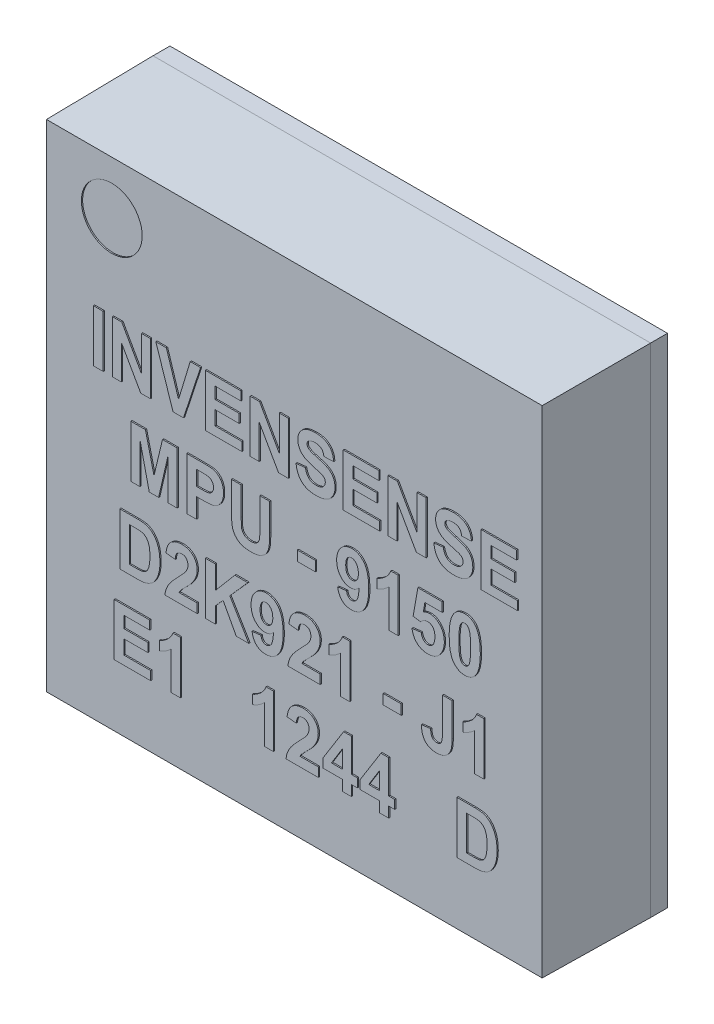
SolidWorks part; units mm, degrees
ref_plane "Front Plane" through (0, 0, 0) normal (0, 0, 1) x (1, 0, 0)
ref_plane "Top Plane" through (0, 0, 0) normal (0, 1, 0) x (1, 0, 0)
ref_plane "Right Plane" through (0, 0, 0) normal (1, 0, 0) x (0, 0, -1)
sketch "Sketch1" plane through (0, 0, 0) normal (0, 0, 1) x (1, 0, 0)
  line L1 (-2, -2) -> (2, -2)
  line L2 (-2, -2) -> (-2, 2)
  line L3 (-2, 2) -> (2, 2)
  line L4 (2, -2) -> (2, 2)
  line L5 (-2, -2) -> (2, 2) construction
  line L6 (-2, 2) -> (2, -2) construction
  point P0 (0, 0)
  dimension "D1" = 4
  dimension "D2" = 4
extrude "Boss-Extrude1" add sketch "Sketch1" along normal blind 0.864 draft 0.5 and the other way blind 0.136
sketch "Sketch2" plane through (0, 0, -0.136) normal (0, 0, -1) x (-1, 0, 0)
  line L0 (-0.875, -1.88) -> (-0.875, -1.53)
  line L1 (-1.25, -1.705) -> (1.25, -1.705) construction
  line L2 (-1.25, -1.705) -> (-1.25, 1.705) construction
  line L3 (-1.25, 1.705) -> (1.25, 1.705) construction
  line L4 (1.25, -1.705) -> (1.25, 1.705) construction
  line L5 (-1.25, -1.705) -> (1.25, 1.705) construction
  line L6 (-1.25, 1.705) -> (1.25, -1.705) construction
  line L7 (-1.375, -1.88) -> (-1.125, -1.88)
  line L8 (-1.375, -1.88) -> (-1.375, -1.53)
  line L9 (-1.375, -1.53) -> (-1.125, -1.53)
  line L10 (-1.125, -1.88) -> (-1.125, -1.53)
  line L11 (-1.375, -1.88) -> (-1.125, -1.53) construction
  line L12 (-1.375, -1.53) -> (-1.125, -1.88) construction
  line L13 (-0.875, -1.53) -> (-0.625, -1.53)
  line L14 (-0.625, -1.88) -> (-0.625, -1.53)
  line L15 (-0.875, -1.88) -> (-0.625, -1.88)
  line L16 (-0.375, -1.88) -> (-0.375, -1.53)
  line L17 (-0.375, -1.53) -> (-0.125, -1.53)
  line L18 (-0.125, -1.88) -> (-0.125, -1.53)
  line L19 (-0.375, -1.88) -> (-0.125, -1.88)
  line L20 (0.125, -1.88) -> (0.125, -1.53)
  line L21 (0.125, -1.53) -> (0.375, -1.53)
  line L22 (0.375, -1.88) -> (0.375, -1.53)
  line L23 (0.125, -1.88) -> (0.375, -1.88)
  line L24 (0.625, -1.88) -> (0.625, -1.53)
  line L25 (0.625, -1.53) -> (0.875, -1.53)
  line L26 (0.875, -1.88) -> (0.875, -1.53)
  line L27 (0.625, -1.88) -> (0.875, -1.88)
  line L28 (1.125, -1.88) -> (1.125, -1.53)
  line L29 (1.125, -1.53) -> (1.375, -1.53)
  line L30 (1.375, -1.88) -> (1.375, -1.53)
  line L31 (1.125, -1.88) -> (1.375, -1.88)
  line L32 (-1.88, 0.875) -> (-1.53, 0.875)
  line L33 (-1.88, 1.375) -> (-1.88, 1.125)
  line L34 (-1.88, 1.375) -> (-1.53, 1.375)
  line L35 (-1.53, 1.375) -> (-1.53, 1.125)
  line L36 (-1.88, 1.125) -> (-1.53, 1.125)
  line L37 (-1.53, 0.875) -> (-1.53, 0.625)
  line L38 (-1.88, 0.625) -> (-1.53, 0.625)
  line L39 (-1.88, 0.875) -> (-1.88, 0.625)
  line L40 (-1.88, 0.375) -> (-1.53, 0.375)
  line L41 (-1.53, 0.375) -> (-1.53, 0.125)
  line L42 (-1.88, 0.125) -> (-1.53, 0.125)
  line L43 (-1.88, 0.375) -> (-1.88, 0.125)
  line L44 (-1.88, -0.125) -> (-1.53, -0.125)
  line L45 (-1.53, -0.125) -> (-1.53, -0.375)
  line L46 (-1.88, -0.375) -> (-1.53, -0.375)
  line L47 (-1.88, -0.125) -> (-1.88, -0.375)
  line L48 (-1.88, -0.625) -> (-1.53, -0.625)
  line L49 (-1.53, -0.625) -> (-1.53, -0.875)
  line L50 (-1.88, -0.875) -> (-1.53, -0.875)
  line L51 (-1.88, -0.625) -> (-1.88, -0.875)
  line L52 (-1.88, -1.125) -> (-1.53, -1.125)
  line L53 (-1.53, -1.125) -> (-1.53, -1.375)
  line L54 (-1.88, -1.375) -> (-1.53, -1.375)
  line L55 (-1.88, -1.125) -> (-1.88, -1.375)
  line L56 (-1.88, 1.375) -> (-1.53, 1.125) construction
  line L57 (-1.53, 1.375) -> (-1.88, 1.125) construction
  line L58 (0.875, 1.88) -> (0.875, 1.53)
  line L59 (1.375, 1.88) -> (1.125, 1.88)
  line L60 (1.375, 1.88) -> (1.375, 1.53)
  line L61 (1.375, 1.53) -> (1.125, 1.53)
  line L62 (1.125, 1.88) -> (1.125, 1.53)
  line L63 (0.875, 1.53) -> (0.625, 1.53)
  line L64 (0.625, 1.88) -> (0.625, 1.53)
  line L65 (0.875, 1.88) -> (0.625, 1.88)
  line L66 (0.375, 1.88) -> (0.375, 1.53)
  line L67 (0.375, 1.53) -> (0.125, 1.53)
  line L68 (0.125, 1.88) -> (0.125, 1.53)
  line L69 (0.375, 1.88) -> (0.125, 1.88)
  line L70 (-0.125, 1.88) -> (-0.125, 1.53)
  line L71 (-0.125, 1.53) -> (-0.375, 1.53)
  line L72 (-0.375, 1.88) -> (-0.375, 1.53)
  line L73 (-0.125, 1.88) -> (-0.375, 1.88)
  line L74 (-0.625, 1.88) -> (-0.625, 1.53)
  line L75 (-0.625, 1.53) -> (-0.875, 1.53)
  line L76 (-0.875, 1.88) -> (-0.875, 1.53)
  line L77 (-0.625, 1.88) -> (-0.875, 1.88)
  line L78 (-1.125, 1.88) -> (-1.125, 1.53)
  line L79 (-1.125, 1.53) -> (-1.375, 1.53)
  line L80 (-1.375, 1.88) -> (-1.375, 1.53)
  line L81 (-1.125, 1.88) -> (-1.375, 1.88)
  line L82 (1.375, 1.88) -> (1.125, 1.53) construction
  line L83 (1.375, 1.53) -> (1.125, 1.88) construction
  line L84 (1.88, -0.875) -> (1.53, -0.875)
  line L85 (1.88, -1.375) -> (1.88, -1.125)
  line L86 (1.88, -1.375) -> (1.53, -1.375)
  line L87 (1.53, -1.375) -> (1.53, -1.125)
  line L88 (1.88, -1.125) -> (1.53, -1.125)
  line L89 (1.53, -0.875) -> (1.53, -0.625)
  line L90 (1.88, -0.625) -> (1.53, -0.625)
  line L91 (1.88, -0.875) -> (1.88, -0.625)
  line L92 (1.88, -0.375) -> (1.53, -0.375)
  line L93 (1.53, -0.375) -> (1.53, -0.125)
  line L94 (1.88, -0.125) -> (1.53, -0.125)
  line L95 (1.88, -0.375) -> (1.88, -0.125)
  line L96 (1.88, 0.125) -> (1.53, 0.125)
  line L97 (1.53, 0.125) -> (1.53, 0.375)
  line L98 (1.88, 0.375) -> (1.53, 0.375)
  line L99 (1.88, 0.125) -> (1.88, 0.375)
  line L100 (1.88, 0.625) -> (1.53, 0.625)
  line L101 (1.53, 0.625) -> (1.53, 0.875)
  line L102 (1.88, 0.875) -> (1.53, 0.875)
  line L103 (1.88, 0.625) -> (1.88, 0.875)
  line L104 (1.88, 1.125) -> (1.53, 1.125)
  line L105 (1.53, 1.125) -> (1.53, 1.375)
  line L106 (1.88, 1.375) -> (1.53, 1.375)
  line L107 (1.88, 1.125) -> (1.88, 1.375)
  line L108 (1.88, -1.375) -> (1.53, -1.125) construction
  line L109 (1.53, -1.375) -> (1.88, -1.125) construction
  point P0 (0, 0)
  point P105 (0, 0)
  dimension "D1" = 2.5
  dimension "D2" = 0.25
  dimension "D3" = 0.35
  dimension "D4" = 3.41
  dimension "D5" = 6
  dimension "D6" = 4
extrude "Boss-Extrude2" add sketch "Sketch2" along normal blind 0.01
sketch "Sketch3" plane through (0, 0, 0.864) normal (0, 0, 1) x (1, 0, 0)
  circle A0 centre (-1.4676, 1.5665) radius 0.2444
extrude "Cut-Extrude1" cut sketch "Sketch3" against normal blind 0.01
sketch "Sketch5" plane through (0, 0, 0.864) normal (0, 0, 1) x (1, 0, 0)
  line L0 (-1.6052, 0.4755) -> (-1.6052, 0.8946)
  line L1 (-1.6052, 0.8946) -> (-1.5271, 0.8946)
  line L2 (-1.5271, 0.8946) -> (-1.5271, 0.4755)
  line L3 (-1.5271, 0.4755) -> (-1.6052, 0.4755)
  line L4 (-1.453, 0.4755) -> (-1.453, 0.8946)
  line L5 (-1.453, 0.8946) -> (-1.3773, 0.8946)
  line L6 (-1.3773, 0.8946) -> (-1.2186, 0.6138)
  line L7 (-1.2186, 0.6138) -> (-1.2186, 0.8946)
  line L8 (-1.2186, 0.8946) -> (-1.1464, 0.8946)
  line L9 (-1.1464, 0.8946) -> (-1.1464, 0.4755)
  line L10 (-1.1464, 0.4755) -> (-1.2245, 0.4755)
  line L11 (-1.2245, 0.4755) -> (-1.3807, 0.751)
  line L12 (-1.3807, 0.751) -> (-1.3807, 0.4755)
  line L13 (-1.3807, 0.4755) -> (-1.453, 0.4755)
  line L14 (-0.9652, 0.4755) -> (-1.1033, 0.8946)
  line L15 (-1.1033, 0.8946) -> (-1.0189, 0.8946)
  line L16 (-1.0189, 0.8946) -> (-0.9209, 0.5844)
  line L17 (-0.9209, 0.5844) -> (-0.8269, 0.8946)
  line L18 (-0.8269, 0.8946) -> (-0.7439, 0.8946)
  line L19 (-0.7439, 0.8946) -> (-0.8811, 0.4755)
  line L20 (-0.8811, 0.4755) -> (-0.9652, 0.4755)
  line L21 (-0.7046, 0.4755) -> (-0.7046, 0.8946)
  line L22 (-0.7046, 0.8946) -> (-0.419, 0.8946)
  line L23 (-0.419, 0.8946) -> (-0.419, 0.8238)
  line L24 (-0.419, 0.8238) -> (-0.6264, 0.8238)
  line L25 (-0.6264, 0.8238) -> (-0.6264, 0.7307)
  line L26 (-0.6264, 0.7307) -> (-0.4336, 0.7307)
  line L27 (-0.4336, 0.7307) -> (-0.4336, 0.6599)
  line L28 (-0.4336, 0.6599) -> (-0.6264, 0.6599)
  line L29 (-0.6264, 0.6599) -> (-0.6264, 0.5463)
  line L30 (-0.6264, 0.5463) -> (-0.4115, 0.5463)
  line L31 (-0.4115, 0.5463) -> (-0.4115, 0.4755)
  line L32 (-0.4115, 0.4755) -> (-0.7046, 0.4755)
  line L33 (-0.3453, 0.4755) -> (-0.3453, 0.8946)
  line L34 (-0.3453, 0.8946) -> (-0.2696, 0.8946)
  line L35 (-0.2696, 0.8946) -> (-0.1109, 0.6138)
  line L36 (-0.1109, 0.6138) -> (-0.1109, 0.8946)
  line L37 (-0.1109, 0.8946) -> (-0.0387, 0.8946)
  line L38 (-0.0387, 0.8946) -> (-0.0387, 0.4755)
  line L39 (-0.0387, 0.4755) -> (-0.1168, 0.4755)
  line L40 (-0.1168, 0.4755) -> (-0.273, 0.751)
  line L41 (-0.273, 0.751) -> (-0.273, 0.4755)
  line L42 (-0.273, 0.4755) -> (-0.3453, 0.4755)
  line L43 (0.0234, 0.6113) -> (0.0993, 0.6195)
  line L44 (0.3256, 0.7741) -> (0.2475, 0.7711)
  line L45 (0.4031, 0.4755) -> (0.4031, 0.8946)
  line L46 (0.4031, 0.8946) -> (0.6887, 0.8946)
  line L47 (0.6887, 0.8946) -> (0.6887, 0.8238)
  line L48 (0.6887, 0.8238) -> (0.4813, 0.8238)
  line L49 (0.4813, 0.8238) -> (0.4813, 0.7307)
  line L50 (0.4813, 0.7307) -> (0.6741, 0.7307)
  line L51 (0.6741, 0.7307) -> (0.6741, 0.6599)
  line L52 (0.6741, 0.6599) -> (0.4813, 0.6599)
  line L53 (0.4813, 0.6599) -> (0.4813, 0.5463)
  line L54 (0.4813, 0.5463) -> (0.6962, 0.5463)
  line L55 (0.6962, 0.5463) -> (0.6962, 0.4755)
  line L56 (0.6962, 0.4755) -> (0.4031, 0.4755)
  line L57 (0.7625, 0.4755) -> (0.7625, 0.8946)
  line L58 (0.7625, 0.8946) -> (0.8382, 0.8946)
  line L59 (0.8382, 0.8946) -> (0.9969, 0.6138)
  line L60 (0.9969, 0.6138) -> (0.9969, 0.8946)
  line L61 (0.9969, 0.8946) -> (1.0691, 0.8946)
  line L62 (1.0691, 0.8946) -> (1.0691, 0.4755)
  line L63 (1.0691, 0.4755) -> (0.991, 0.4755)
  line L64 (0.991, 0.4755) -> (0.8348, 0.751)
  line L65 (0.8348, 0.751) -> (0.8348, 0.4755)
  line L66 (0.8348, 0.4755) -> (0.7625, 0.4755)
  line L67 (1.1312, 0.6113) -> (1.2071, 0.6195)
  line L68 (1.4334, 0.7741) -> (1.3553, 0.7711)
  line L69 (1.5109, 0.4755) -> (1.5109, 0.8946)
  line L70 (1.5109, 0.8946) -> (1.7965, 0.8946)
  line L71 (1.7965, 0.8946) -> (1.7965, 0.8238)
  line L72 (1.7965, 0.8238) -> (1.5891, 0.8238)
  line L73 (1.5891, 0.8238) -> (1.5891, 0.7307)
  line L74 (1.5891, 0.7307) -> (1.7819, 0.7307)
  line L75 (1.7819, 0.7307) -> (1.7819, 0.6599)
  line L76 (1.7819, 0.6599) -> (1.5891, 0.6599)
  line L77 (1.5891, 0.6599) -> (1.5891, 0.5463)
  line L78 (1.5891, 0.5463) -> (1.804, 0.5463)
  line L79 (1.804, 0.5463) -> (1.804, 0.4755)
  line L80 (1.804, 0.4755) -> (1.5109, 0.4755)
  line L81 (-1.3043, -0.1785) -> (-1.3043, 0.2406)
  line L82 (-1.3043, 0.2406) -> (-1.1873, 0.2406)
  line L83 (-1.1873, 0.2406) -> (-1.1182, -0.0452)
  line L84 (-1.1182, -0.0452) -> (-1.0498, 0.2406)
  line L85 (-1.0498, 0.2406) -> (-0.9326, 0.2406)
  line L86 (-0.9326, 0.2406) -> (-0.9326, -0.1785)
  line L87 (-0.9326, -0.1785) -> (-1.0048, -0.1785)
  line L88 (-1.0048, -0.1785) -> (-1.005, 0.1515)
  line L89 (-1.005, 0.1515) -> (-1.0811, -0.1785)
  line L90 (-1.0811, -0.1785) -> (-1.1562, -0.1785)
  line L91 (-1.1562, -0.1785) -> (-1.2319, 0.1515)
  line L92 (-1.2319, 0.1515) -> (-1.2321, -0.1785)
  line L93 (-1.2321, -0.1785) -> (-1.3043, -0.1785)
  line L94 (-0.8546, -0.1785) -> (-0.8546, 0.2406)
  line L95 (-0.8546, 0.2406) -> (-0.7297, 0.2406)
  line L96 (-0.7258, -0.0204) -> (-0.7764, -0.0204)
  line L97 (-0.7764, -0.0204) -> (-0.7764, -0.1785)
  line L98 (-0.7764, -0.1785) -> (-0.8546, -0.1785)
  line L99 (-0.7764, 0.1698) -> (-0.7764, 0.0504)
  line L100 (-0.7764, 0.0504) -> (-0.7339, 0.0504)
  line L101 (-0.739, 0.1698) -> (-0.7764, 0.1698)
  line L102 (-0.4953, 0.2406) -> (-0.4171, 0.2406)
  line L103 (-0.4171, 0.2406) -> (-0.4171, 0.0135)
  line L104 (-0.2669, 0.0086) -> (-0.2669, 0.2406)
  line L105 (-0.2669, 0.2406) -> (-0.1887, 0.2406)
  line L106 (-0.1887, 0.2406) -> (-0.1887, 0.0202)
  line L107 (-0.4953, 0.0168) -> (-0.4953, 0.2406)
  line L108 (0.0343, -0.0667) -> (0.0343, 0.0135)
  line L109 (0.0343, 0.0135) -> (0.1797, 0.0135)
  line L110 (0.1797, 0.0135) -> (0.1797, -0.0667)
  line L111 (0.1797, -0.0667) -> (0.0343, -0.0667)
  line L112 (0.3584, -0.0811) -> (0.4301, -0.0725)
  line L113 (0.8445, -0.1785) -> (0.7707, -0.1785)
  line L114 (0.7707, -0.1785) -> (0.7707, 0.1249)
  line L115 (0.6753, 0.0639) -> (0.6753, 0.137)
  line L116 (0.7846, 0.243) -> (0.8445, 0.243)
  line L117 (0.8445, 0.243) -> (0.8445, -0.1785)
  line L118 (0.9562, -0.0709) -> (1.03, -0.0626)
  line L119 (1.0251, 0.0082) -> (0.9653, 0.0176)
  line L120 (0.9653, 0.0176) -> (1.003, 0.2354)
  line L121 (1.003, 0.2354) -> (1.1986, 0.2354)
  line L122 (1.1986, 0.2354) -> (1.1986, 0.1604)
  line L123 (1.1986, 0.1604) -> (1.0592, 0.1604)
  line L124 (1.0592, 0.1604) -> (1.0475, 0.0891)
  line L125 (-1.3935, -0.4134) -> (-1.2514, -0.4134)
  line L126 (-1.2472, -0.8325) -> (-1.3935, -0.8325)
  line L127 (-1.3935, -0.8325) -> (-1.3935, -0.4134)
  line L128 (-1.3153, -0.4842) -> (-1.3153, -0.7617)
  line L129 (-1.3153, -0.7617) -> (-1.2575, -0.7617)
  line L130 (-1.2805, -0.4842) -> (-1.3153, -0.4842)
  line L131 (-0.7711, -0.7582) -> (-0.7711, -0.8325)
  line L132 (-0.7711, -0.8325) -> (-1.0302, -0.8325)
  line L133 (-0.9478, -0.5433) -> (-1.0216, -0.5353)
  line L134 (-0.9181, -0.7582) -> (-0.7711, -0.7582)
  line L135 (-0.7037, -0.8325) -> (-0.7037, -0.4134)
  line L136 (-0.7037, -0.4134) -> (-0.6255, -0.4134)
  line L137 (-0.6255, -0.4134) -> (-0.6255, -0.599)
  line L138 (-0.6255, -0.599) -> (-0.4682, -0.4134)
  line L139 (-0.4682, -0.4134) -> (-0.3635, -0.4134)
  line L140 (-0.3635, -0.4134) -> (-0.509, -0.5766)
  line L141 (-0.509, -0.5766) -> (-0.3559, -0.8325)
  line L142 (-0.3559, -0.8325) -> (-0.4567, -0.8325)
  line L143 (-0.4567, -0.8325) -> (-0.5628, -0.6357)
  line L144 (-0.5628, -0.6357) -> (-0.6255, -0.7058)
  line L145 (-0.6255, -0.7058) -> (-0.6255, -0.8325)
  line L146 (-0.6255, -0.8325) -> (-0.7037, -0.8325)
  line L147 (-0.3297, -0.7351) -> (-0.258, -0.7265)
  line L148 (0.2172, -0.7582) -> (0.2172, -0.8325)
  line L149 (0.2172, -0.8325) -> (-0.0419, -0.8325)
  line L150 (0.0405, -0.5433) -> (-0.0333, -0.5353)
  line L151 (0.0702, -0.7582) -> (0.2172, -0.7582)
  line L152 (0.456, -0.8325) -> (0.3822, -0.8325)
  line L153 (0.3822, -0.8325) -> (0.3822, -0.5291)
  line L154 (0.2868, -0.5901) -> (0.2868, -0.517)
  line L155 (0.3961, -0.411) -> (0.456, -0.411)
  line L156 (0.456, -0.411) -> (0.456, -0.8325)
  line L157 (0.7237, -0.7207) -> (0.7237, -0.6405)
  line L158 (0.7237, -0.6405) -> (0.8691, -0.6405)
  line L159 (0.8691, -0.6405) -> (0.8691, -0.7207)
  line L160 (0.8691, -0.7207) -> (0.7237, -0.7207)
  line L161 (1.2002, -0.4134) -> (1.2783, -0.4134)
  line L162 (1.2783, -0.4134) -> (1.2783, -0.6789)
  line L163 (1.0316, -0.7037) -> (1.1054, -0.6943)
  line L164 (1.2002, -0.6843) -> (1.2002, -0.4134)
  line L165 (1.5339, -0.8325) -> (1.4601, -0.8325)
  line L166 (1.4601, -0.8325) -> (1.4601, -0.5291)
  line L167 (1.3647, -0.5901) -> (1.3647, -0.517)
  line L168 (1.474, -0.411) -> (1.5339, -0.411)
  line L169 (1.5339, -0.411) -> (1.5339, -0.8325)
  line L170 (-1.4384, -1.4865) -> (-1.4384, -1.0674)
  line L171 (-1.4384, -1.0674) -> (-1.1528, -1.0674)
  line L172 (-1.1528, -1.0674) -> (-1.1528, -1.1382)
  line L173 (-1.1528, -1.1382) -> (-1.3602, -1.1382)
  line L174 (-1.3602, -1.1382) -> (-1.3602, -1.2313)
  line L175 (-1.3602, -1.2313) -> (-1.1674, -1.2313)
  line L176 (-1.1674, -1.2313) -> (-1.1674, -1.3021)
  line L177 (-1.1674, -1.3021) -> (-1.3602, -1.3021)
  line L178 (-1.3602, -1.3021) -> (-1.3602, -1.4157)
  line L179 (-1.3602, -1.4157) -> (-1.1453, -1.4157)
  line L180 (-1.1453, -1.4157) -> (-1.1453, -1.4865)
  line L181 (-1.1453, -1.4865) -> (-1.4384, -1.4865)
  line L182 (-0.9065, -1.4865) -> (-0.9803, -1.4865)
  line L183 (-0.9803, -1.4865) -> (-0.9803, -1.1831)
  line L184 (-1.0757, -1.2441) -> (-1.0757, -1.171)
  line L185 (-0.9664, -1.065) -> (-0.9065, -1.065)
  line L186 (-0.9065, -1.065) -> (-0.9065, -1.4865)
  line L187 (-0.158, -1.4865) -> (-0.2318, -1.4865)
  line L188 (-0.2318, -1.4865) -> (-0.2318, -1.1831)
  line L189 (-0.3272, -1.2441) -> (-0.3272, -1.171)
  line L190 (-0.2179, -1.065) -> (-0.158, -1.065)
  line L191 (-0.158, -1.065) -> (-0.158, -1.4865)
  line L192 (0.2024, -1.4122) -> (0.2024, -1.4865)
  line L193 (0.2024, -1.4865) -> (-0.0567, -1.4865)
  line L194 (0.0257, -1.1973) -> (-0.0481, -1.1893)
  line L195 (0.0554, -1.4122) -> (0.2024, -1.4122)
  line L196 (0.397, -1.4865) -> (0.397, -1.4022)
  line L197 (0.397, -1.4022) -> (0.2397, -1.4022)
  line L198 (0.2397, -1.4022) -> (0.2397, -1.3322)
  line L199 (0.2397, -1.3322) -> (0.4065, -1.0656)
  line L200 (0.4065, -1.0656) -> (0.4686, -1.0656)
  line L201 (0.4686, -1.0656) -> (0.4686, -1.332)
  line L202 (0.4686, -1.332) -> (0.5165, -1.332)
  line L203 (0.5165, -1.332) -> (0.5165, -1.4022)
  line L204 (0.5165, -1.4022) -> (0.4686, -1.4022)
  line L205 (0.4686, -1.4022) -> (0.4686, -1.4865)
  line L206 (0.4686, -1.4865) -> (0.397, -1.4865)
  line L207 (0.397, -1.332) -> (0.397, -1.1888)
  line L208 (0.397, -1.1888) -> (0.3088, -1.332)
  line L209 (0.3088, -1.332) -> (0.397, -1.332)
  line L210 (0.6966, -1.4865) -> (0.6966, -1.4022)
  line L211 (0.6966, -1.4022) -> (0.5393, -1.4022)
  line L212 (0.5393, -1.4022) -> (0.5393, -1.3322)
  line L213 (0.5393, -1.3322) -> (0.7061, -1.0656)
  line L214 (0.7061, -1.0656) -> (0.7682, -1.0656)
  line L215 (0.7682, -1.0656) -> (0.7682, -1.332)
  line L216 (0.7682, -1.332) -> (0.8161, -1.332)
  line L217 (0.8161, -1.332) -> (0.8161, -1.4022)
  line L218 (0.8161, -1.4022) -> (0.7682, -1.4022)
  line L219 (0.7682, -1.4022) -> (0.7682, -1.4865)
  line L220 (0.7682, -1.4865) -> (0.6966, -1.4865)
  line L221 (0.6966, -1.332) -> (0.6966, -1.1888)
  line L222 (0.6966, -1.1888) -> (0.6084, -1.332)
  line L223 (0.6084, -1.332) -> (0.6966, -1.332)
  line L224 (1.3168, -1.0674) -> (1.4589, -1.0674)
  line L225 (1.4631, -1.4865) -> (1.3168, -1.4865)
  line L226 (1.3168, -1.4865) -> (1.3168, -1.0674)
  line L227 (1.395, -1.1382) -> (1.395, -1.4157)
  line L228 (1.395, -1.4157) -> (1.4528, -1.4157)
  line L229 (1.4298, -1.1382) -> (1.395, -1.1382)
  spline S0 degree 3 poles (0.0993, 0.6195) (0.1039, 0.5919) (0.1131, 0.5717) (0.127, 0.5587) knots 0.032258 0.032258 0.032258 0.032258 0.064516 0.064516 0.064516 0.064516
  spline S1 degree 3 poles (0.127, 0.5587) (0.1409, 0.5457) (0.1597, 0.5393) (0.1833, 0.5393) knots 0.064516 0.064516 0.064516 0.064516 0.096774 0.096774 0.096774 0.096774
  spline S2 degree 3 poles (0.1833, 0.5393) (0.2083, 0.5393) (0.2271, 0.5451) (0.2397, 0.5566) knots 0.096774 0.096774 0.096774 0.096774 0.129032 0.129032 0.129032 0.129032
  spline S3 degree 3 poles (0.2397, 0.5566) (0.2524, 0.5681) (0.2588, 0.5816) (0.2588, 0.597) knots 0.129032 0.129032 0.129032 0.129032 0.16129 0.16129 0.16129 0.16129
  spline S4 degree 3 poles (0.2588, 0.597) (0.2588, 0.6069) (0.2561, 0.6153) (0.2508, 0.6223) knots 0.16129 0.16129 0.16129 0.16129 0.193548 0.193548 0.193548 0.193548
  spline S5 degree 3 poles (0.2508, 0.6223) (0.2455, 0.6293) (0.2362, 0.6353) (0.2229, 0.6404) knots 0.193548 0.193548 0.193548 0.193548 0.225806 0.225806 0.225806 0.225806
  spline S6 degree 3 poles (0.2229, 0.6404) (0.2138, 0.6439) (0.1932, 0.6499) (0.1609, 0.6587) knots 0.225806 0.225806 0.225806 0.225806 0.258065 0.258065 0.258065 0.258065
  spline S7 degree 3 poles (0.1609, 0.6587) (0.1193, 0.67) (0.0901, 0.6839) (0.0733, 0.7004) knots 0.258065 0.258065 0.258065 0.258065 0.290323 0.290323 0.290323 0.290323
  spline S8 degree 3 poles (0.0733, 0.7004) (0.0497, 0.7235) (0.0379, 0.7517) (0.0379, 0.785) knots 0.290323 0.290323 0.290323 0.290323 0.322581 0.322581 0.322581 0.322581
  spline S9 degree 3 poles (0.0379, 0.785) (0.0379, 0.8063) (0.0435, 0.8264) (0.0545, 0.8451) knots 0.322581 0.322581 0.322581 0.322581 0.354839 0.354839 0.354839 0.354839
  spline S10 degree 3 poles (0.0545, 0.8451) (0.0656, 0.8637) (0.0817, 0.8779) (0.1025, 0.8876) knots 0.354839 0.354839 0.354839 0.354839 0.387097 0.387097 0.387097 0.387097
  spline S11 degree 3 poles (0.1025, 0.8876) (0.1235, 0.8974) (0.1486, 0.9023) (0.1783, 0.9023) knots 0.387097 0.387097 0.387097 0.387097 0.419355 0.419355 0.419355 0.419355
  spline S12 degree 3 poles (0.1783, 0.9023) (0.2265, 0.9023) (0.2628, 0.8906) (0.2871, 0.8673) knots 0.419355 0.419355 0.419355 0.419355 0.451613 0.451613 0.451613 0.451613
  spline S13 degree 3 poles (0.2871, 0.8673) (0.3116, 0.844) (0.3243, 0.813) (0.3256, 0.7741) knots 0.451613 0.451613 0.451613 0.451613 0.483871 0.483871 0.483871 0.483871
  spline S14 degree 3 poles (0.2475, 0.7711) (0.2442, 0.7928) (0.2371, 0.8083) (0.2262, 0.8178) knots 0.516129 0.516129 0.516129 0.516129 0.548387 0.548387 0.548387 0.548387
  spline S15 degree 3 poles (0.2262, 0.8178) (0.2154, 0.8272) (0.199, 0.832) (0.1773, 0.832) knots 0.548387 0.548387 0.548387 0.548387 0.580645 0.580645 0.580645 0.580645
  spline S16 degree 3 poles (0.1773, 0.832) (0.1548, 0.832) (0.1372, 0.8269) (0.1245, 0.8168) knots 0.580645 0.580645 0.580645 0.580645 0.612903 0.612903 0.612903 0.612903
  spline S17 degree 3 poles (0.1245, 0.8168) (0.1164, 0.8103) (0.1123, 0.8016) (0.1123, 0.7906) knots 0.612903 0.612903 0.612903 0.612903 0.645161 0.645161 0.645161 0.645161
  spline S18 degree 3 poles (0.1123, 0.7906) (0.1123, 0.7807) (0.1162, 0.7722) (0.1239, 0.7652) knots 0.645161 0.645161 0.645161 0.645161 0.677419 0.677419 0.677419 0.677419
  spline S19 degree 3 poles (0.1239, 0.7652) (0.1336, 0.7561) (0.1575, 0.7467) (0.1952, 0.737) knots 0.677419 0.677419 0.677419 0.677419 0.709677 0.709677 0.709677 0.709677
  spline S20 degree 3 poles (0.1952, 0.737) (0.233, 0.7273) (0.261, 0.7172) (0.279, 0.7068) knots 0.709677 0.709677 0.709677 0.709677 0.741935 0.741935 0.741935 0.741935
  spline S21 degree 3 poles (0.279, 0.7068) (0.2972, 0.6964) (0.3113, 0.6822) (0.3216, 0.6642) knots 0.741935 0.741935 0.741935 0.741935 0.774194 0.774194 0.774194 0.774194
  spline S22 degree 3 poles (0.3216, 0.6642) (0.3318, 0.6461) (0.3369, 0.6239) (0.3369, 0.5975) knots 0.774194 0.774194 0.774194 0.774194 0.806452 0.806452 0.806452 0.806452
  spline S23 degree 3 poles (0.3369, 0.5975) (0.3369, 0.5735) (0.3308, 0.5509) (0.3185, 0.5299) knots 0.806452 0.806452 0.806452 0.806452 0.83871 0.83871 0.83871 0.83871
  spline S24 degree 3 poles (0.3185, 0.5299) (0.3062, 0.509) (0.2889, 0.4934) (0.2664, 0.4832) knots 0.83871 0.83871 0.83871 0.83871 0.870968 0.870968 0.870968 0.870968
  spline S25 degree 3 poles (0.2664, 0.4832) (0.244, 0.473) (0.216, 0.4679) (0.1825, 0.4679) knots 0.870968 0.870968 0.870968 0.870968 0.903226 0.903226 0.903226 0.903226
  spline S26 degree 3 poles (0.1825, 0.4679) (0.1337, 0.4679) (0.0963, 0.4801) (0.0701, 0.5046) knots 0.903226 0.903226 0.903226 0.903226 0.935484 0.935484 0.935484 0.935484
  spline S27 degree 3 poles (0.0701, 0.5046) (0.044, 0.529) (0.0286, 0.5646) (0.0234, 0.6113) knots 0.935484 0.935484 0.935484 0.935484 1 1 1 1
  spline S28 degree 3 poles (1.2071, 0.6195) (1.2117, 0.5919) (1.2209, 0.5717) (1.2348, 0.5587) knots 0.032258 0.032258 0.032258 0.032258 0.064516 0.064516 0.064516 0.064516
  spline S29 degree 3 poles (1.2348, 0.5587) (1.2487, 0.5457) (1.2675, 0.5393) (1.2911, 0.5393) knots 0.064516 0.064516 0.064516 0.064516 0.096774 0.096774 0.096774 0.096774
  spline S30 degree 3 poles (1.2911, 0.5393) (1.3161, 0.5393) (1.3349, 0.5451) (1.3475, 0.5566) knots 0.096774 0.096774 0.096774 0.096774 0.129032 0.129032 0.129032 0.129032
  spline S31 degree 3 poles (1.3475, 0.5566) (1.3602, 0.5681) (1.3666, 0.5816) (1.3666, 0.597) knots 0.129032 0.129032 0.129032 0.129032 0.16129 0.16129 0.16129 0.16129
  spline S32 degree 3 poles (1.3666, 0.597) (1.3666, 0.6069) (1.3639, 0.6153) (1.3586, 0.6223) knots 0.16129 0.16129 0.16129 0.16129 0.193548 0.193548 0.193548 0.193548
  spline S33 degree 3 poles (1.3586, 0.6223) (1.3533, 0.6293) (1.344, 0.6353) (1.3307, 0.6404) knots 0.193548 0.193548 0.193548 0.193548 0.225806 0.225806 0.225806 0.225806
  spline S34 degree 3 poles (1.3307, 0.6404) (1.3216, 0.6439) (1.301, 0.6499) (1.2687, 0.6587) knots 0.225806 0.225806 0.225806 0.225806 0.258065 0.258065 0.258065 0.258065
  spline S35 degree 3 poles (1.2687, 0.6587) (1.2271, 0.67) (1.1979, 0.6839) (1.1811, 0.7004) knots 0.258065 0.258065 0.258065 0.258065 0.290323 0.290323 0.290323 0.290323
  spline S36 degree 3 poles (1.1811, 0.7004) (1.1575, 0.7235) (1.1457, 0.7517) (1.1457, 0.785) knots 0.290323 0.290323 0.290323 0.290323 0.322581 0.322581 0.322581 0.322581
  spline S37 degree 3 poles (1.1457, 0.785) (1.1457, 0.8063) (1.1513, 0.8264) (1.1623, 0.8451) knots 0.322581 0.322581 0.322581 0.322581 0.354839 0.354839 0.354839 0.354839
  spline S38 degree 3 poles (1.1623, 0.8451) (1.1734, 0.8637) (1.1895, 0.8779) (1.2103, 0.8876) knots 0.354839 0.354839 0.354839 0.354839 0.387097 0.387097 0.387097 0.387097
  spline S39 degree 3 poles (1.2103, 0.8876) (1.2313, 0.8974) (1.2564, 0.9023) (1.2861, 0.9023) knots 0.387097 0.387097 0.387097 0.387097 0.419355 0.419355 0.419355 0.419355
  spline S40 degree 3 poles (1.2861, 0.9023) (1.3343, 0.9023) (1.3706, 0.8906) (1.3949, 0.8673) knots 0.419355 0.419355 0.419355 0.419355 0.451613 0.451613 0.451613 0.451613
  spline S41 degree 3 poles (1.3949, 0.8673) (1.4194, 0.844) (1.4321, 0.813) (1.4334, 0.7741) knots 0.451613 0.451613 0.451613 0.451613 0.483871 0.483871 0.483871 0.483871
  spline S42 degree 3 poles (1.3553, 0.7711) (1.352, 0.7928) (1.3449, 0.8083) (1.334, 0.8178) knots 0.516129 0.516129 0.516129 0.516129 0.548387 0.548387 0.548387 0.548387
  spline S43 degree 3 poles (1.334, 0.8178) (1.3232, 0.8272) (1.3068, 0.832) (1.2851, 0.832) knots 0.548387 0.548387 0.548387 0.548387 0.580645 0.580645 0.580645 0.580645
  spline S44 degree 3 poles (1.2851, 0.832) (1.2626, 0.832) (1.245, 0.8269) (1.2323, 0.8168) knots 0.580645 0.580645 0.580645 0.580645 0.612903 0.612903 0.612903 0.612903
  spline S45 degree 3 poles (1.2323, 0.8168) (1.2242, 0.8103) (1.2201, 0.8016) (1.2201, 0.7906) knots 0.612903 0.612903 0.612903 0.612903 0.645161 0.645161 0.645161 0.645161
  spline S46 degree 3 poles (1.2201, 0.7906) (1.2201, 0.7807) (1.224, 0.7722) (1.2317, 0.7652) knots 0.645161 0.645161 0.645161 0.645161 0.677419 0.677419 0.677419 0.677419
  spline S47 degree 3 poles (1.2317, 0.7652) (1.2414, 0.7561) (1.2653, 0.7467) (1.303, 0.737) knots 0.677419 0.677419 0.677419 0.677419 0.709677 0.709677 0.709677 0.709677
  spline S48 degree 3 poles (1.303, 0.737) (1.3408, 0.7273) (1.3688, 0.7172) (1.3868, 0.7068) knots 0.709677 0.709677 0.709677 0.709677 0.741935 0.741935 0.741935 0.741935
  spline S49 degree 3 poles (1.3868, 0.7068) (1.405, 0.6964) (1.4191, 0.6822) (1.4294, 0.6642) knots 0.741935 0.741935 0.741935 0.741935 0.774194 0.774194 0.774194 0.774194
  spline S50 degree 3 poles (1.4294, 0.6642) (1.4396, 0.6461) (1.4447, 0.6239) (1.4447, 0.5975) knots 0.774194 0.774194 0.774194 0.774194 0.806452 0.806452 0.806452 0.806452
  spline S51 degree 3 poles (1.4447, 0.5975) (1.4447, 0.5735) (1.4386, 0.5509) (1.4263, 0.5299) knots 0.806452 0.806452 0.806452 0.806452 0.83871 0.83871 0.83871 0.83871
  spline S52 degree 3 poles (1.4263, 0.5299) (1.414, 0.509) (1.3967, 0.4934) (1.3742, 0.4832) knots 0.83871 0.83871 0.83871 0.83871 0.870968 0.870968 0.870968 0.870968
  spline S53 degree 3 poles (1.3742, 0.4832) (1.3518, 0.473) (1.3238, 0.4679) (1.2903, 0.4679) knots 0.870968 0.870968 0.870968 0.870968 0.903226 0.903226 0.903226 0.903226
  spline S54 degree 3 poles (1.2903, 0.4679) (1.2415, 0.4679) (1.2041, 0.4801) (1.1779, 0.5046) knots 0.903226 0.903226 0.903226 0.903226 0.935484 0.935484 0.935484 0.935484
  spline S55 degree 3 poles (1.1779, 0.5046) (1.1518, 0.529) (1.1364, 0.5646) (1.1312, 0.6113) knots 0.935484 0.935484 0.935484 0.935484 1 1 1 1
  spline S56 degree 3 poles (-0.7297, 0.2406) (-0.6823, 0.2406) (-0.6516, 0.2386) (-0.6372, 0.2344) knots 0.153846 0.153846 0.153846 0.153846 0.230769 0.230769 0.230769 0.230769
  spline S57 degree 3 poles (-0.6372, 0.2344) (-0.6151, 0.2281) (-0.5966, 0.2144) (-0.5817, 0.1933) knots 0.230769 0.230769 0.230769 0.230769 0.307692 0.307692 0.307692 0.307692
  spline S58 degree 3 poles (-0.5817, 0.1933) (-0.5668, 0.1723) (-0.5594, 0.145) (-0.5594, 0.1117) knots 0.307692 0.307692 0.307692 0.307692 0.384615 0.384615 0.384615 0.384615
  spline S59 degree 3 poles (-0.5594, 0.1117) (-0.5594, 0.0859) (-0.5636, 0.0643) (-0.5722, 0.0468) knots 0.384615 0.384615 0.384615 0.384615 0.461538 0.461538 0.461538 0.461538
  spline S60 degree 3 poles (-0.5722, 0.0468) (-0.5808, 0.0292) (-0.5917, 0.0155) (-0.6048, 0.0054) knots 0.461538 0.461538 0.461538 0.461538 0.538462 0.538462 0.538462 0.538462
  spline S61 degree 3 poles (-0.6048, 0.0054) (-0.6181, -0.0045) (-0.6315, -0.0112) (-0.6451, -0.0144) knots 0.538462 0.538462 0.538462 0.538462 0.615385 0.615385 0.615385 0.615385
  spline S62 degree 3 poles (-0.6451, -0.0144) (-0.6637, -0.0184) (-0.6906, -0.0204) (-0.7258, -0.0204) knots 0.615385 0.615385 0.615385 0.615385 0.692308 0.692308 0.692308 0.692308
  spline S63 degree 3 poles (-0.7339, 0.0504) (-0.7034, 0.0504) (-0.6829, 0.0526) (-0.6726, 0.057) knots 0.2 0.2 0.2 0.2 0.3 0.3 0.3 0.3
  spline S64 degree 3 poles (-0.6726, 0.057) (-0.6623, 0.0614) (-0.6542, 0.0682) (-0.6484, 0.0777) knots 0.3 0.3 0.3 0.3 0.4 0.4 0.4 0.4
  spline S65 degree 3 poles (-0.6484, 0.0777) (-0.6426, 0.0871) (-0.6396, 0.0979) (-0.6396, 0.1104) knots 0.4 0.4 0.4 0.4 0.5 0.5 0.5 0.5
  spline S66 degree 3 poles (-0.6396, 0.1104) (-0.6396, 0.1257) (-0.6437, 0.1383) (-0.6519, 0.1483) knots 0.5 0.5 0.5 0.5 0.6 0.6 0.6 0.6
  spline S67 degree 3 poles (-0.6519, 0.1483) (-0.6601, 0.1582) (-0.6705, 0.1644) (-0.6831, 0.167) knots 0.6 0.6 0.6 0.6 0.7 0.7 0.7 0.7
  spline S68 degree 3 poles (-0.6831, 0.167) (-0.6924, 0.1688) (-0.711, 0.1698) (-0.739, 0.1698) knots 0.7 0.7 0.7 0.7 0.8 0.8 0.8 0.8
  spline S69 degree 3 poles (-0.4171, 0.0135) (-0.4171, -0.0226) (-0.4161, -0.0459) (-0.4143, -0.0565) knots 0.095238 0.095238 0.095238 0.095238 0.142857 0.142857 0.142857 0.142857
  spline S70 degree 3 poles (-0.4143, -0.0565) (-0.411, -0.0737) (-0.4032, -0.0876) (-0.3907, -0.0979) knots 0.142857 0.142857 0.142857 0.142857 0.190476 0.190476 0.190476 0.190476
  spline S71 degree 3 poles (-0.3907, -0.0979) (-0.3782, -0.1083) (-0.3613, -0.1135) (-0.3398, -0.1135) knots 0.190476 0.190476 0.190476 0.190476 0.238095 0.238095 0.238095 0.238095
  spline S72 degree 3 poles (-0.3398, -0.1135) (-0.3179, -0.1135) (-0.3014, -0.1086) (-0.2902, -0.0988) knots 0.238095 0.238095 0.238095 0.238095 0.285714 0.285714 0.285714 0.285714
  spline S73 degree 3 poles (-0.2902, -0.0988) (-0.2791, -0.0889) (-0.2725, -0.0769) (-0.2703, -0.0626) knots 0.285714 0.285714 0.285714 0.285714 0.333333 0.333333 0.333333 0.333333
  spline S74 degree 3 poles (-0.2703, -0.0626) (-0.268, -0.0482) (-0.2669, -0.0245) (-0.2669, 0.0086) knots 0.333333 0.333333 0.333333 0.333333 0.380952 0.380952 0.380952 0.380952
  spline S75 degree 3 poles (-0.1887, 0.0202) (-0.1887, -0.0301) (-0.1908, -0.0657) (-0.195, -0.0865) knots 0.52381 0.52381 0.52381 0.52381 0.571429 0.571429 0.571429 0.571429
  spline S76 degree 3 poles (-0.195, -0.0865) (-0.1992, -0.1073) (-0.207, -0.1248) (-0.2183, -0.1392) knots 0.571429 0.571429 0.571429 0.571429 0.619048 0.619048 0.619048 0.619048
  spline S77 degree 3 poles (-0.2183, -0.1392) (-0.2295, -0.1535) (-0.2446, -0.1648) (-0.2634, -0.1733) knots 0.619048 0.619048 0.619048 0.619048 0.666667 0.666667 0.666667 0.666667
  spline S78 degree 3 poles (-0.2634, -0.1733) (-0.2823, -0.1818) (-0.307, -0.1861) (-0.3374, -0.1861) knots 0.666667 0.666667 0.666667 0.666667 0.714286 0.714286 0.714286 0.714286
  spline S79 degree 3 poles (-0.3374, -0.1861) (-0.3741, -0.1861) (-0.402, -0.1815) (-0.4209, -0.1723) knots 0.714286 0.714286 0.714286 0.714286 0.761905 0.761905 0.761905 0.761905
  spline S80 degree 3 poles (-0.4209, -0.1723) (-0.4399, -0.163) (-0.4549, -0.151) (-0.4659, -0.1362) knots 0.761905 0.761905 0.761905 0.761905 0.809524 0.809524 0.809524 0.809524
  spline S81 degree 3 poles (-0.4659, -0.1362) (-0.477, -0.1213) (-0.4841, -0.1059) (-0.4876, -0.0896) knots 0.809524 0.809524 0.809524 0.809524 0.857143 0.857143 0.857143 0.857143
  spline S82 degree 3 poles (-0.4876, -0.0896) (-0.4927, -0.0656) (-0.4953, -0.0301) (-0.4953, 0.0168) knots 0.857143 0.857143 0.857143 0.857143 0.904762 0.904762 0.904762 0.904762
  spline S83 degree 3 poles (0.4301, -0.0725) (0.4318, -0.0884) (0.4364, -0.1003) (0.4437, -0.1079) knots 0.058824 0.058824 0.058824 0.058824 0.117647 0.117647 0.117647 0.117647
  spline S84 degree 3 poles (0.4437, -0.1079) (0.4509, -0.1156) (0.4606, -0.1194) (0.4726, -0.1194) knots 0.117647 0.117647 0.117647 0.117647 0.176471 0.176471 0.176471 0.176471
  spline S85 degree 3 poles (0.4726, -0.1194) (0.4877, -0.1194) (0.5006, -0.1117) (0.5112, -0.0963) knots 0.176471 0.176471 0.176471 0.176471 0.235294 0.235294 0.235294 0.235294
  spline S86 degree 3 poles (0.5112, -0.0963) (0.5218, -0.081) (0.5285, -0.0492) (0.5314, -0.0011) knots 0.235294 0.235294 0.235294 0.235294 0.294118 0.294118 0.294118 0.294118
  spline S87 degree 3 poles (0.5314, -0.0011) (0.5129, -0.0245) (0.4898, -0.0362) (0.4618, -0.0362) knots 0.294118 0.294118 0.294118 0.294118 0.352941 0.352941 0.352941 0.352941
  spline S88 degree 3 poles (0.4618, -0.0362) (0.4315, -0.0362) (0.4053, -0.0236) (0.3833, 0.0019) knots 0.352941 0.352941 0.352941 0.352941 0.411765 0.411765 0.411765 0.411765
  spline S89 degree 3 poles (0.3833, 0.0019) (0.3613, 0.0274) (0.3503, 0.0604) (0.3503, 0.1012) knots 0.411765 0.411765 0.411765 0.411765 0.470588 0.470588 0.470588 0.470588
  spline S90 degree 3 poles (0.3503, 0.1012) (0.3503, 0.1438) (0.3619, 0.178) (0.3852, 0.204) knots 0.470588 0.470588 0.470588 0.470588 0.529412 0.529412 0.529412 0.529412
  spline S91 degree 3 poles (0.3852, 0.204) (0.4085, 0.23) (0.4381, 0.243) (0.474, 0.243) knots 0.529412 0.529412 0.529412 0.529412 0.588235 0.588235 0.588235 0.588235
  spline S92 degree 3 poles (0.474, 0.243) (0.513, 0.243) (0.5452, 0.2265) (0.5703, 0.1936) knots 0.588235 0.588235 0.588235 0.588235 0.647059 0.647059 0.647059 0.647059
  spline S93 degree 3 poles (0.5703, 0.1936) (0.5953, 0.1606) (0.6079, 0.1065) (0.6079, 0.031) knots 0.647059 0.647059 0.647059 0.647059 0.705882 0.705882 0.705882 0.705882
  spline S94 degree 3 poles (0.6079, 0.031) (0.6079, -0.0457) (0.5948, -0.1011) (0.5688, -0.1351) knots 0.705882 0.705882 0.705882 0.705882 0.764706 0.764706 0.764706 0.764706
  spline S95 degree 3 poles (0.5688, -0.1351) (0.5428, -0.1691) (0.5088, -0.1861) (0.467, -0.1861) knots 0.764706 0.764706 0.764706 0.764706 0.823529 0.823529 0.823529 0.823529
  spline S96 degree 3 poles (0.467, -0.1861) (0.4369, -0.1861) (0.4126, -0.1773) (0.3941, -0.1598) knots 0.823529 0.823529 0.823529 0.823529 0.882353 0.882353 0.882353 0.882353
  spline S97 degree 3 poles (0.3941, -0.1598) (0.3756, -0.1423) (0.3637, -0.1161) (0.3584, -0.0811) knots 0.882353 0.882353 0.882353 0.882353 1 1 1 1
  spline S98 degree 3 poles (0.5249, 0.0947) (0.5249, 0.1205) (0.5195, 0.1406) (0.5084, 0.1549) knots 0 0 0 0 0.111111 0.111111 0.111111 0.111111
  spline S99 degree 3 poles (0.5084, 0.1549) (0.4976, 0.1691) (0.485, 0.1763) (0.4706, 0.1763) knots 0.111111 0.111111 0.111111 0.111111 0.222222 0.222222 0.222222 0.222222
  spline S100 degree 3 poles (0.4706, 0.1763) (0.4569, 0.1763) (0.4457, 0.1704) (0.4367, 0.1587) knots 0.222222 0.222222 0.222222 0.222222 0.333333 0.333333 0.333333 0.333333
  spline S101 degree 3 poles (0.4367, 0.1587) (0.4276, 0.147) (0.4231, 0.1279) (0.4231, 0.1013) knots 0.333333 0.333333 0.333333 0.333333 0.444444 0.444444 0.444444 0.444444
  spline S102 degree 3 poles (0.4231, 0.1013) (0.4231, 0.0743) (0.428, 0.0545) (0.4379, 0.0418) knots 0.444444 0.444444 0.444444 0.444444 0.555556 0.555556 0.555556 0.555556
  spline S103 degree 3 poles (0.4379, 0.0418) (0.4476, 0.0292) (0.4599, 0.0229) (0.4746, 0.0229) knots 0.555556 0.555556 0.555556 0.555556 0.666667 0.666667 0.666667 0.666667
  spline S104 degree 3 poles (0.4746, 0.0229) (0.4887, 0.0229) (0.5007, 0.0289) (0.5104, 0.0411) knots 0.666667 0.666667 0.666667 0.666667 0.777778 0.777778 0.777778 0.777778
  spline S105 degree 3 poles (0.5104, 0.0411) (0.52, 0.0533) (0.5249, 0.0712) (0.5249, 0.0947) knots 0.777778 0.777778 0.777778 0.777778 1 1 1 1
  spline S106 degree 3 poles (0.7707, 0.1249) (0.7437, 0.0974) (0.712, 0.077) (0.6753, 0.0639) knots 0.222222 0.222222 0.222222 0.222222 0.333333 0.333333 0.333333 0.333333
  spline S107 degree 3 poles (0.6753, 0.137) (0.6946, 0.1439) (0.7156, 0.1568) (0.738, 0.1761) knots 0.444444 0.444444 0.444444 0.444444 0.555556 0.555556 0.555556 0.555556
  spline S108 degree 3 poles (0.738, 0.1761) (0.7606, 0.1952) (0.7761, 0.2175) (0.7846, 0.243) knots 0.555556 0.555556 0.555556 0.555556 0.666667 0.666667 0.666667 0.666667
  spline S109 degree 3 poles (1.03, -0.0626) (1.0321, -0.0807) (1.0383, -0.0952) (1.0487, -0.1058) knots 0.045455 0.045455 0.045455 0.045455 0.090909 0.090909 0.090909 0.090909
  spline S110 degree 3 poles (1.0487, -0.1058) (1.0591, -0.1164) (1.0709, -0.1217) (1.0845, -0.1217) knots 0.090909 0.090909 0.090909 0.090909 0.136364 0.136364 0.136364 0.136364
  spline S111 degree 3 poles (1.0845, -0.1217) (1.1, -0.1217) (1.1131, -0.1149) (1.1238, -0.1011) knots 0.136364 0.136364 0.136364 0.136364 0.181818 0.181818 0.181818 0.181818
  spline S112 degree 3 poles (1.1238, -0.1011) (1.1344, -0.0874) (1.1399, -0.0667) (1.1399, -0.0391) knots 0.181818 0.181818 0.181818 0.181818 0.227273 0.227273 0.227273 0.227273
  spline S113 degree 3 poles (1.1399, -0.0391) (1.1399, -0.0131) (1.1345, 0.0063) (1.1238, 0.0193) knots 0.227273 0.227273 0.227273 0.227273 0.272727 0.272727 0.272727 0.272727
  spline S114 degree 3 poles (1.1238, 0.0193) (1.1133, 0.0322) (1.0995, 0.0387) (1.0823, 0.0387) knots 0.272727 0.272727 0.272727 0.272727 0.318182 0.318182 0.318182 0.318182
  spline S115 degree 3 poles (1.0823, 0.0387) (1.0611, 0.0387) (1.0419, 0.0285) (1.0251, 0.0082) knots 0.318182 0.318182 0.318182 0.318182 0.363636 0.363636 0.363636 0.363636
  spline S116 degree 3 poles (1.0475, 0.0891) (1.0638, 0.098) (1.0808, 0.1025) (1.098, 0.1025) knots 0.636364 0.636364 0.636364 0.636364 0.681818 0.681818 0.681818 0.681818
  spline S117 degree 3 poles (1.098, 0.1025) (1.1308, 0.1025) (1.1587, 0.0895) (1.1814, 0.0635) knots 0.681818 0.681818 0.681818 0.681818 0.727273 0.727273 0.727273 0.727273
  spline S118 degree 3 poles (1.1814, 0.0635) (1.2044, 0.0375) (1.2158, 0.0038) (1.2158, -0.0378) knots 0.727273 0.727273 0.727273 0.727273 0.772727 0.772727 0.772727 0.772727
  spline S119 degree 3 poles (1.2158, -0.0378) (1.2158, -0.0724) (1.2066, -0.1033) (1.1882, -0.1305) knots 0.772727 0.772727 0.772727 0.772727 0.818182 0.818182 0.818182 0.818182
  spline S120 degree 3 poles (1.1882, -0.1305) (1.163, -0.1676) (1.1282, -0.1861) (1.0836, -0.1861) knots 0.818182 0.818182 0.818182 0.818182 0.863636 0.863636 0.863636 0.863636
  spline S121 degree 3 poles (1.0836, -0.1861) (1.048, -0.1861) (1.0189, -0.1757) (0.9965, -0.1549) knots 0.863636 0.863636 0.863636 0.863636 0.909091 0.909091 0.909091 0.909091
  spline S122 degree 3 poles (0.9965, -0.1549) (0.9739, -0.134) (0.9605, -0.1061) (0.9562, -0.0709) knots 0.909091 0.909091 0.909091 0.909091 1 1 1 1
  spline S123 degree 3 poles (1.3799, 0.243) (1.4173, 0.243) (1.4464, 0.2285) (1.4675, 0.1994) knots 0 0 0 0 0.111111 0.111111 0.111111 0.111111
  spline S124 degree 3 poles (1.4675, 0.1994) (1.4926, 0.165) (1.5052, 0.108) (1.5052, 0.0283) knots 0.111111 0.111111 0.111111 0.111111 0.222222 0.222222 0.222222 0.222222
  spline S125 degree 3 poles (1.5052, 0.0283) (1.5052, -0.0512) (1.4925, -0.1083) (1.4672, -0.1431) knots 0.222222 0.222222 0.222222 0.222222 0.333333 0.333333 0.333333 0.333333
  spline S126 degree 3 poles (1.4672, -0.1431) (1.4464, -0.1718) (1.4173, -0.1861) (1.3799, -0.1861) knots 0.333333 0.333333 0.333333 0.333333 0.444444 0.444444 0.444444 0.444444
  spline S127 degree 3 poles (1.3799, -0.1861) (1.3424, -0.1861) (1.3121, -0.1704) (1.2892, -0.139) knots 0.444444 0.444444 0.444444 0.444444 0.555556 0.555556 0.555556 0.555556
  spline S128 degree 3 poles (1.2892, -0.139) (1.2662, -0.1076) (1.2547, -0.0515) (1.2547, 0.0291) knots 0.555556 0.555556 0.555556 0.555556 0.666667 0.666667 0.666667 0.666667
  spline S129 degree 3 poles (1.2547, 0.0291) (1.2547, 0.1082) (1.2673, 0.1652) (1.2926, 0.2) knots 0.666667 0.666667 0.666667 0.666667 0.777778 0.777778 0.777778 0.777778
  spline S130 degree 3 poles (1.2926, 0.2) (1.3135, 0.2286) (1.3426, 0.243) (1.3799, 0.243) knots 0.777778 0.777778 0.777778 0.777778 1 1 1 1
  spline S131 degree 3 poles (1.3799, 0.1763) (1.3711, 0.1763) (1.3632, 0.1731) (1.3564, 0.1669) knots 0 0 0 0 0.076923 0.076923 0.076923 0.076923
  spline S132 degree 3 poles (1.3564, 0.1669) (1.3495, 0.1607) (1.3441, 0.1496) (1.3403, 0.1335) knots 0.076923 0.076923 0.076923 0.076923 0.153846 0.153846 0.153846 0.153846
  spline S133 degree 3 poles (1.3403, 0.1335) (1.3353, 0.1127) (1.3328, 0.0776) (1.3328, 0.0283) knots 0.153846 0.153846 0.153846 0.153846 0.230769 0.230769 0.230769 0.230769
  spline S134 degree 3 poles (1.3328, 0.0283) (1.3328, -0.021) (1.335, -0.0549) (1.3395, -0.0733) knots 0.230769 0.230769 0.230769 0.230769 0.307692 0.307692 0.307692 0.307692
  spline S135 degree 3 poles (1.3395, -0.0733) (1.344, -0.0918) (1.3496, -0.1041) (1.3565, -0.1102) knots 0.307692 0.307692 0.307692 0.307692 0.384615 0.384615 0.384615 0.384615
  spline S136 degree 3 poles (1.3565, -0.1102) (1.3633, -0.1164) (1.3711, -0.1194) (1.3799, -0.1194) knots 0.384615 0.384615 0.384615 0.384615 0.461538 0.461538 0.461538 0.461538
  spline S137 degree 3 poles (1.3799, -0.1194) (1.3888, -0.1194) (1.3966, -0.1163) (1.4036, -0.11) knots 0.461538 0.461538 0.461538 0.461538 0.538462 0.538462 0.538462 0.538462
  spline S138 degree 3 poles (1.4036, -0.11) (1.4104, -0.1039) (1.4157, -0.0927) (1.4195, -0.0766) knots 0.538462 0.538462 0.538462 0.538462 0.615385 0.615385 0.615385 0.615385
  spline S139 degree 3 poles (1.4195, -0.0766) (1.4245, -0.0561) (1.427, -0.021) (1.427, 0.0283) knots 0.615385 0.615385 0.615385 0.615385 0.692308 0.692308 0.692308 0.692308
  spline S140 degree 3 poles (1.427, 0.0283) (1.427, 0.0776) (1.4248, 0.1115) (1.4203, 0.1299) knots 0.692308 0.692308 0.692308 0.692308 0.769231 0.769231 0.769231 0.769231
  spline S141 degree 3 poles (1.4203, 0.1299) (1.4158, 0.1483) (1.4102, 0.1607) (1.4034, 0.1669) knots 0.769231 0.769231 0.769231 0.769231 0.846154 0.846154 0.846154 0.846154
  spline S142 degree 3 poles (1.4034, 0.1669) (1.3965, 0.1731) (1.3888, 0.1763) (1.3799, 0.1763) knots 0.846154 0.846154 0.846154 0.846154 1 1 1 1
  spline S143 degree 3 poles (-1.2514, -0.4134) (-1.2194, -0.4134) (-1.1949, -0.416) (-1.1781, -0.4214) knots 0.083333 0.083333 0.083333 0.083333 0.166667 0.166667 0.166667 0.166667
  spline S144 degree 3 poles (-1.1781, -0.4214) (-1.1556, -0.4286) (-1.1362, -0.4415) (-1.1202, -0.46) knots 0.166667 0.166667 0.166667 0.166667 0.25 0.25 0.25 0.25
  spline S145 degree 3 poles (-1.1202, -0.46) (-1.104, -0.4784) (-1.0917, -0.5011) (-1.0834, -0.5279) knots 0.25 0.25 0.25 0.25 0.333333 0.333333 0.333333 0.333333
  spline S146 degree 3 poles (-1.0834, -0.5279) (-1.075, -0.5546) (-1.0707, -0.5877) (-1.0707, -0.6269) knots 0.333333 0.333333 0.333333 0.333333 0.416667 0.416667 0.416667 0.416667
  spline S147 degree 3 poles (-1.0707, -0.6269) (-1.0707, -0.6615) (-1.0747, -0.6911) (-1.0826, -0.7161) knots 0.416667 0.416667 0.416667 0.416667 0.5 0.5 0.5 0.5
  spline S148 degree 3 poles (-1.0826, -0.7161) (-1.0922, -0.7466) (-1.106, -0.7713) (-1.1238, -0.7902) knots 0.5 0.5 0.5 0.5 0.583333 0.583333 0.583333 0.583333
  spline S149 degree 3 poles (-1.1238, -0.7902) (-1.1373, -0.8045) (-1.1555, -0.8156) (-1.1784, -0.8236) knots 0.583333 0.583333 0.583333 0.583333 0.666667 0.666667 0.666667 0.666667
  spline S150 degree 3 poles (-1.1784, -0.8236) (-1.1955, -0.8296) (-1.2184, -0.8325) (-1.2472, -0.8325) knots 0.666667 0.666667 0.666667 0.666667 0.75 0.75 0.75 0.75
  spline S151 degree 3 poles (-1.2575, -0.7617) (-1.2357, -0.7617) (-1.2202, -0.7603) (-1.2105, -0.7577) knots 0.166667 0.166667 0.166667 0.166667 0.25 0.25 0.25 0.25
  spline S152 degree 3 poles (-1.2105, -0.7577) (-1.1979, -0.7543) (-1.1874, -0.7484) (-1.1792, -0.7402) knots 0.25 0.25 0.25 0.25 0.333333 0.333333 0.333333 0.333333
  spline S153 degree 3 poles (-1.1792, -0.7402) (-1.1709, -0.732) (-1.1642, -0.7185) (-1.1589, -0.6998) knots 0.333333 0.333333 0.333333 0.333333 0.416667 0.416667 0.416667 0.416667
  spline S154 degree 3 poles (-1.1589, -0.6998) (-1.1537, -0.6811) (-1.151, -0.6554) (-1.151, -0.623) knots 0.416667 0.416667 0.416667 0.416667 0.5 0.5 0.5 0.5
  spline S155 degree 3 poles (-1.151, -0.623) (-1.151, -0.5906) (-1.1537, -0.5659) (-1.1589, -0.5485) knots 0.5 0.5 0.5 0.5 0.583333 0.583333 0.583333 0.583333
  spline S156 degree 3 poles (-1.1589, -0.5485) (-1.1642, -0.5311) (-1.1715, -0.5177) (-1.1809, -0.5079) knots 0.583333 0.583333 0.583333 0.583333 0.666667 0.666667 0.666667 0.666667
  spline S157 degree 3 poles (-1.1809, -0.5079) (-1.1904, -0.4982) (-1.2022, -0.4916) (-1.2169, -0.4882) knots 0.666667 0.666667 0.666667 0.666667 0.75 0.75 0.75 0.75
  spline S158 degree 3 poles (-1.2169, -0.4882) (-1.2276, -0.4856) (-1.2489, -0.4842) (-1.2805, -0.4842) knots 0.75 0.75 0.75 0.75 0.833333 0.833333 0.833333 0.833333
  spline S159 degree 3 poles (-1.0302, -0.8325) (-1.0274, -0.8042) (-1.019, -0.7775) (-1.0049, -0.7522) knots 0.090909 0.090909 0.090909 0.090909 0.136364 0.136364 0.136364 0.136364
  spline S160 degree 3 poles (-1.0049, -0.7522) (-0.9909, -0.7269) (-0.9632, -0.6934) (-0.9219, -0.6515) knots 0.136364 0.136364 0.136364 0.136364 0.181818 0.181818 0.181818 0.181818
  spline S161 degree 3 poles (-0.9219, -0.6515) (-0.8886, -0.6178) (-0.8683, -0.5948) (-0.8607, -0.5828) knots 0.181818 0.181818 0.181818 0.181818 0.227273 0.227273 0.227273 0.227273
  spline S162 degree 3 poles (-0.8607, -0.5828) (-0.8505, -0.5662) (-0.8454, -0.5498) (-0.8454, -0.5336) knots 0.227273 0.227273 0.227273 0.227273 0.272727 0.272727 0.272727 0.272727
  spline S163 degree 3 poles (-0.8454, -0.5336) (-0.8454, -0.5156) (-0.8499, -0.5018) (-0.8587, -0.4922) knots 0.272727 0.272727 0.272727 0.272727 0.318182 0.318182 0.318182 0.318182
  spline S164 degree 3 poles (-0.8587, -0.4922) (-0.8675, -0.4825) (-0.8797, -0.4777) (-0.8952, -0.4777) knots 0.318182 0.318182 0.318182 0.318182 0.363636 0.363636 0.363636 0.363636
  spline S165 degree 3 poles (-0.8952, -0.4777) (-0.9107, -0.4777) (-0.9229, -0.4828) (-0.932, -0.493) knots 0.363636 0.363636 0.363636 0.363636 0.409091 0.409091 0.409091 0.409091
  spline S166 degree 3 poles (-0.932, -0.493) (-0.9412, -0.503) (-0.9463, -0.5198) (-0.9478, -0.5433) knots 0.409091 0.409091 0.409091 0.409091 0.454545 0.454545 0.454545 0.454545
  spline S167 degree 3 poles (-1.0216, -0.5353) (-1.0172, -0.491) (-1.0034, -0.4592) (-0.9803, -0.4399) knots 0.5 0.5 0.5 0.5 0.545455 0.545455 0.545455 0.545455
  spline S168 degree 3 poles (-0.9803, -0.4399) (-0.9571, -0.4207) (-0.9282, -0.411) (-0.8935, -0.411) knots 0.545455 0.545455 0.545455 0.545455 0.590909 0.590909 0.590909 0.590909
  spline S169 degree 3 poles (-0.8935, -0.411) (-0.8554, -0.411) (-0.8255, -0.4222) (-0.8037, -0.4446) knots 0.590909 0.590909 0.590909 0.590909 0.636364 0.636364 0.636364 0.636364
  spline S170 degree 3 poles (-0.8037, -0.4446) (-0.782, -0.4669) (-0.7711, -0.4947) (-0.7711, -0.528) knots 0.636364 0.636364 0.636364 0.636364 0.681818 0.681818 0.681818 0.681818
  spline S171 degree 3 poles (-0.7711, -0.528) (-0.7711, -0.5469) (-0.7742, -0.5649) (-0.7804, -0.582) knots 0.681818 0.681818 0.681818 0.681818 0.727273 0.727273 0.727273 0.727273
  spline S172 degree 3 poles (-0.7804, -0.582) (-0.7866, -0.5991) (-0.7965, -0.617) (-0.81, -0.6357) knots 0.727273 0.727273 0.727273 0.727273 0.772727 0.772727 0.772727 0.772727
  spline S173 degree 3 poles (-0.81, -0.6357) (-0.8189, -0.6482) (-0.8352, -0.6661) (-0.8585, -0.6894) knots 0.772727 0.772727 0.772727 0.772727 0.818182 0.818182 0.818182 0.818182
  spline S174 degree 3 poles (-0.8585, -0.6894) (-0.882, -0.7127) (-0.8968, -0.7281) (-0.903, -0.7358) knots 0.818182 0.818182 0.818182 0.818182 0.863636 0.863636 0.863636 0.863636
  spline S175 degree 3 poles (-0.903, -0.7358) (-0.9092, -0.7434) (-0.9143, -0.7509) (-0.9181, -0.7582) knots 0.863636 0.863636 0.863636 0.863636 0.909091 0.909091 0.909091 0.909091
  spline S176 degree 3 poles (-0.258, -0.7265) (-0.2563, -0.7424) (-0.2517, -0.7543) (-0.2444, -0.7619) knots 0.058824 0.058824 0.058824 0.058824 0.117647 0.117647 0.117647 0.117647
  spline S177 degree 3 poles (-0.2444, -0.7619) (-0.2372, -0.7696) (-0.2275, -0.7734) (-0.2155, -0.7734) knots 0.117647 0.117647 0.117647 0.117647 0.176471 0.176471 0.176471 0.176471
  spline S178 degree 3 poles (-0.2155, -0.7734) (-0.2004, -0.7734) (-0.1875, -0.7657) (-0.1769, -0.7503) knots 0.176471 0.176471 0.176471 0.176471 0.235294 0.235294 0.235294 0.235294
  spline S179 degree 3 poles (-0.1769, -0.7503) (-0.1663, -0.735) (-0.1596, -0.7032) (-0.1567, -0.6551) knots 0.235294 0.235294 0.235294 0.235294 0.294118 0.294118 0.294118 0.294118
  spline S180 degree 3 poles (-0.1567, -0.6551) (-0.1752, -0.6785) (-0.1983, -0.6902) (-0.2263, -0.6902) knots 0.294118 0.294118 0.294118 0.294118 0.352941 0.352941 0.352941 0.352941
  spline S181 degree 3 poles (-0.2263, -0.6902) (-0.2566, -0.6902) (-0.2828, -0.6776) (-0.3048, -0.6521) knots 0.352941 0.352941 0.352941 0.352941 0.411765 0.411765 0.411765 0.411765
  spline S182 degree 3 poles (-0.3048, -0.6521) (-0.3268, -0.6266) (-0.3378, -0.5936) (-0.3378, -0.5528) knots 0.411765 0.411765 0.411765 0.411765 0.470588 0.470588 0.470588 0.470588
  spline S183 degree 3 poles (-0.3378, -0.5528) (-0.3378, -0.5102) (-0.3262, -0.476) (-0.3029, -0.45) knots 0.470588 0.470588 0.470588 0.470588 0.529412 0.529412 0.529412 0.529412
  spline S184 degree 3 poles (-0.3029, -0.45) (-0.2796, -0.424) (-0.25, -0.411) (-0.2141, -0.411) knots 0.529412 0.529412 0.529412 0.529412 0.588235 0.588235 0.588235 0.588235
  spline S185 degree 3 poles (-0.2141, -0.411) (-0.1751, -0.411) (-0.1429, -0.4275) (-0.1178, -0.4604) knots 0.588235 0.588235 0.588235 0.588235 0.647059 0.647059 0.647059 0.647059
  spline S186 degree 3 poles (-0.1178, -0.4604) (-0.0928, -0.4934) (-0.0802, -0.5475) (-0.0802, -0.623) knots 0.647059 0.647059 0.647059 0.647059 0.705882 0.705882 0.705882 0.705882
  spline S187 degree 3 poles (-0.0802, -0.623) (-0.0802, -0.6997) (-0.0933, -0.7551) (-0.1193, -0.7891) knots 0.705882 0.705882 0.705882 0.705882 0.764706 0.764706 0.764706 0.764706
  spline S188 degree 3 poles (-0.1193, -0.7891) (-0.1453, -0.8231) (-0.1793, -0.8401) (-0.2211, -0.8401) knots 0.764706 0.764706 0.764706 0.764706 0.823529 0.823529 0.823529 0.823529
  spline S189 degree 3 poles (-0.2211, -0.8401) (-0.2512, -0.8401) (-0.2755, -0.8313) (-0.294, -0.8138) knots 0.823529 0.823529 0.823529 0.823529 0.882353 0.882353 0.882353 0.882353
  spline S190 degree 3 poles (-0.294, -0.8138) (-0.3125, -0.7963) (-0.3244, -0.7701) (-0.3297, -0.7351) knots 0.882353 0.882353 0.882353 0.882353 1 1 1 1
  spline S191 degree 3 poles (-0.1632, -0.5593) (-0.1632, -0.5335) (-0.1686, -0.5134) (-0.1797, -0.4991) knots 0 0 0 0 0.111111 0.111111 0.111111 0.111111
  spline S192 degree 3 poles (-0.1797, -0.4991) (-0.1905, -0.4849) (-0.2031, -0.4777) (-0.2175, -0.4777) knots 0.111111 0.111111 0.111111 0.111111 0.222222 0.222222 0.222222 0.222222
  spline S193 degree 3 poles (-0.2175, -0.4777) (-0.2312, -0.4777) (-0.2424, -0.4836) (-0.2514, -0.4953) knots 0.222222 0.222222 0.222222 0.222222 0.333333 0.333333 0.333333 0.333333
  spline S194 degree 3 poles (-0.2514, -0.4953) (-0.2605, -0.507) (-0.265, -0.5261) (-0.265, -0.5527) knots 0.333333 0.333333 0.333333 0.333333 0.444444 0.444444 0.444444 0.444444
  spline S195 degree 3 poles (-0.265, -0.5527) (-0.265, -0.5797) (-0.2601, -0.5995) (-0.2502, -0.6122) knots 0.444444 0.444444 0.444444 0.444444 0.555556 0.555556 0.555556 0.555556
  spline S196 degree 3 poles (-0.2502, -0.6122) (-0.2405, -0.6248) (-0.2282, -0.6311) (-0.2135, -0.6311) knots 0.555556 0.555556 0.555556 0.555556 0.666667 0.666667 0.666667 0.666667
  spline S197 degree 3 poles (-0.2135, -0.6311) (-0.1994, -0.6311) (-0.1874, -0.6251) (-0.1777, -0.6129) knots 0.666667 0.666667 0.666667 0.666667 0.777778 0.777778 0.777778 0.777778
  spline S198 degree 3 poles (-0.1777, -0.6129) (-0.1681, -0.6007) (-0.1632, -0.5828) (-0.1632, -0.5593) knots 0.777778 0.777778 0.777778 0.777778 1 1 1 1
  spline S199 degree 3 poles (-0.0419, -0.8325) (-0.0391, -0.8042) (-0.0307, -0.7775) (-0.0166, -0.7522) knots 0.090909 0.090909 0.090909 0.090909 0.136364 0.136364 0.136364 0.136364
  spline S200 degree 3 poles (-0.0166, -0.7522) (-0.0026, -0.7269) (0.0251, -0.6934) (0.0664, -0.6515) knots 0.136364 0.136364 0.136364 0.136364 0.181818 0.181818 0.181818 0.181818
  spline S201 degree 3 poles (0.0664, -0.6515) (0.0997, -0.6178) (0.12, -0.5948) (0.1276, -0.5828) knots 0.181818 0.181818 0.181818 0.181818 0.227273 0.227273 0.227273 0.227273
  spline S202 degree 3 poles (0.1276, -0.5828) (0.1378, -0.5662) (0.1429, -0.5498) (0.1429, -0.5336) knots 0.227273 0.227273 0.227273 0.227273 0.272727 0.272727 0.272727 0.272727
  spline S203 degree 3 poles (0.1429, -0.5336) (0.1429, -0.5156) (0.1384, -0.5018) (0.1296, -0.4922) knots 0.272727 0.272727 0.272727 0.272727 0.318182 0.318182 0.318182 0.318182
  spline S204 degree 3 poles (0.1296, -0.4922) (0.1208, -0.4825) (0.1086, -0.4777) (0.0931, -0.4777) knots 0.318182 0.318182 0.318182 0.318182 0.363636 0.363636 0.363636 0.363636
  spline S205 degree 3 poles (0.0931, -0.4777) (0.0776, -0.4777) (0.0654, -0.4828) (0.0563, -0.493) knots 0.363636 0.363636 0.363636 0.363636 0.409091 0.409091 0.409091 0.409091
  spline S206 degree 3 poles (0.0563, -0.493) (0.0471, -0.503) (0.042, -0.5198) (0.0405, -0.5433) knots 0.409091 0.409091 0.409091 0.409091 0.454545 0.454545 0.454545 0.454545
  spline S207 degree 3 poles (-0.0333, -0.5353) (-0.0289, -0.491) (-0.0151, -0.4592) (0.008, -0.4399) knots 0.5 0.5 0.5 0.5 0.545455 0.545455 0.545455 0.545455
  spline S208 degree 3 poles (0.008, -0.4399) (0.0312, -0.4207) (0.0601, -0.411) (0.0948, -0.411) knots 0.545455 0.545455 0.545455 0.545455 0.590909 0.590909 0.590909 0.590909
  spline S209 degree 3 poles (0.0948, -0.411) (0.1329, -0.411) (0.1628, -0.4222) (0.1846, -0.4446) knots 0.590909 0.590909 0.590909 0.590909 0.636364 0.636364 0.636364 0.636364
  spline S210 degree 3 poles (0.1846, -0.4446) (0.2063, -0.4669) (0.2172, -0.4947) (0.2172, -0.528) knots 0.636364 0.636364 0.636364 0.636364 0.681818 0.681818 0.681818 0.681818
  spline S211 degree 3 poles (0.2172, -0.528) (0.2172, -0.5469) (0.2141, -0.5649) (0.2079, -0.582) knots 0.681818 0.681818 0.681818 0.681818 0.727273 0.727273 0.727273 0.727273
  spline S212 degree 3 poles (0.2079, -0.582) (0.2017, -0.5991) (0.1918, -0.617) (0.1783, -0.6357) knots 0.727273 0.727273 0.727273 0.727273 0.772727 0.772727 0.772727 0.772727
  spline S213 degree 3 poles (0.1783, -0.6357) (0.1694, -0.6482) (0.1531, -0.6661) (0.1298, -0.6894) knots 0.772727 0.772727 0.772727 0.772727 0.818182 0.818182 0.818182 0.818182
  spline S214 degree 3 poles (0.1298, -0.6894) (0.1063, -0.7127) (0.0915, -0.7281) (0.0853, -0.7358) knots 0.818182 0.818182 0.818182 0.818182 0.863636 0.863636 0.863636 0.863636
  spline S215 degree 3 poles (0.0853, -0.7358) (0.0791, -0.7434) (0.074, -0.7509) (0.0702, -0.7582) knots 0.863636 0.863636 0.863636 0.863636 0.909091 0.909091 0.909091 0.909091
  spline S216 degree 3 poles (0.3822, -0.5291) (0.3552, -0.5566) (0.3235, -0.577) (0.2868, -0.5901) knots 0.222222 0.222222 0.222222 0.222222 0.333333 0.333333 0.333333 0.333333
  spline S217 degree 3 poles (0.2868, -0.517) (0.3061, -0.5101) (0.3271, -0.4972) (0.3495, -0.4779) knots 0.444444 0.444444 0.444444 0.444444 0.555556 0.555556 0.555556 0.555556
  spline S218 degree 3 poles (0.3495, -0.4779) (0.3721, -0.4588) (0.3876, -0.4365) (0.3961, -0.411) knots 0.555556 0.555556 0.555556 0.555556 0.666667 0.666667 0.666667 0.666667
  spline S219 degree 3 poles (1.2783, -0.6789) (1.2783, -0.7137) (1.2755, -0.7404) (1.2699, -0.7591) knots 0.142857 0.142857 0.142857 0.142857 0.214286 0.214286 0.214286 0.214286
  spline S220 degree 3 poles (1.2699, -0.7591) (1.2623, -0.7835) (1.2487, -0.8031) (1.2288, -0.818) knots 0.214286 0.214286 0.214286 0.214286 0.285714 0.285714 0.285714 0.285714
  spline S221 degree 3 poles (1.2288, -0.818) (1.2091, -0.8327) (1.1829, -0.8401) (1.1504, -0.8401) knots 0.285714 0.285714 0.285714 0.285714 0.357143 0.357143 0.357143 0.357143
  spline S222 degree 3 poles (1.1504, -0.8401) (1.1124, -0.8401) (1.0832, -0.8286) (1.0627, -0.8055) knots 0.357143 0.357143 0.357143 0.357143 0.428571 0.428571 0.428571 0.428571
  spline S223 degree 3 poles (1.0627, -0.8055) (1.0421, -0.7824) (1.0317, -0.7484) (1.0316, -0.7037) knots 0.428571 0.428571 0.428571 0.428571 0.5 0.5 0.5 0.5
  spline S224 degree 3 poles (1.1054, -0.6943) (1.1063, -0.7182) (1.1094, -0.7351) (1.115, -0.745) knots 0.571429 0.571429 0.571429 0.571429 0.642857 0.642857 0.642857 0.642857
  spline S225 degree 3 poles (1.115, -0.745) (1.1234, -0.76) (1.136, -0.7675) (1.1531, -0.7675) knots 0.642857 0.642857 0.642857 0.642857 0.714286 0.714286 0.714286 0.714286
  spline S226 degree 3 poles (1.1531, -0.7675) (1.1702, -0.7675) (1.1825, -0.7622) (1.1895, -0.7513) knots 0.714286 0.714286 0.714286 0.714286 0.785714 0.785714 0.785714 0.785714
  spline S227 degree 3 poles (1.1895, -0.7513) (1.1966, -0.7406) (1.2002, -0.7182) (1.2002, -0.6843) knots 0.785714 0.785714 0.785714 0.785714 0.857143 0.857143 0.857143 0.857143
  spline S228 degree 3 poles (1.4601, -0.5291) (1.4331, -0.5566) (1.4014, -0.577) (1.3647, -0.5901) knots 0.222222 0.222222 0.222222 0.222222 0.333333 0.333333 0.333333 0.333333
  spline S229 degree 3 poles (1.3647, -0.517) (1.384, -0.5101) (1.405, -0.4972) (1.4274, -0.4779) knots 0.444444 0.444444 0.444444 0.444444 0.555556 0.555556 0.555556 0.555556
  spline S230 degree 3 poles (1.4274, -0.4779) (1.45, -0.4588) (1.4655, -0.4365) (1.474, -0.411) knots 0.555556 0.555556 0.555556 0.555556 0.666667 0.666667 0.666667 0.666667
  spline S231 degree 3 poles (-0.9803, -1.1831) (-1.0073, -1.2106) (-1.039, -1.231) (-1.0757, -1.2441) knots 0.222222 0.222222 0.222222 0.222222 0.333333 0.333333 0.333333 0.333333
  spline S232 degree 3 poles (-1.0757, -1.171) (-1.0564, -1.1641) (-1.0354, -1.1512) (-1.013, -1.1319) knots 0.444444 0.444444 0.444444 0.444444 0.555556 0.555556 0.555556 0.555556
  spline S233 degree 3 poles (-1.013, -1.1319) (-0.9904, -1.1128) (-0.9749, -1.0905) (-0.9664, -1.065) knots 0.555556 0.555556 0.555556 0.555556 0.666667 0.666667 0.666667 0.666667
  spline S234 degree 3 poles (-0.2318, -1.1831) (-0.2588, -1.2106) (-0.2905, -1.231) (-0.3272, -1.2441) knots 0.222222 0.222222 0.222222 0.222222 0.333333 0.333333 0.333333 0.333333
  spline S235 degree 3 poles (-0.3272, -1.171) (-0.3079, -1.1641) (-0.2869, -1.1512) (-0.2645, -1.1319) knots 0.444444 0.444444 0.444444 0.444444 0.555556 0.555556 0.555556 0.555556
  spline S236 degree 3 poles (-0.2645, -1.1319) (-0.2419, -1.1128) (-0.2264, -1.0905) (-0.2179, -1.065) knots 0.555556 0.555556 0.555556 0.555556 0.666667 0.666667 0.666667 0.666667
  spline S237 degree 3 poles (-0.0567, -1.4865) (-0.0539, -1.4582) (-0.0455, -1.4315) (-0.0314, -1.4062) knots 0.090909 0.090909 0.090909 0.090909 0.136364 0.136364 0.136364 0.136364
  spline S238 degree 3 poles (-0.0314, -1.4062) (-0.0174, -1.3809) (0.0103, -1.3474) (0.0516, -1.3055) knots 0.136364 0.136364 0.136364 0.136364 0.181818 0.181818 0.181818 0.181818
  spline S239 degree 3 poles (0.0516, -1.3055) (0.0849, -1.2718) (0.1052, -1.2488) (0.1128, -1.2368) knots 0.181818 0.181818 0.181818 0.181818 0.227273 0.227273 0.227273 0.227273
  spline S240 degree 3 poles (0.1128, -1.2368) (0.123, -1.2202) (0.1281, -1.2038) (0.1281, -1.1876) knots 0.227273 0.227273 0.227273 0.227273 0.272727 0.272727 0.272727 0.272727
  spline S241 degree 3 poles (0.1281, -1.1876) (0.1281, -1.1696) (0.1236, -1.1558) (0.1148, -1.1462) knots 0.272727 0.272727 0.272727 0.272727 0.318182 0.318182 0.318182 0.318182
  spline S242 degree 3 poles (0.1148, -1.1462) (0.106, -1.1365) (0.0938, -1.1317) (0.0783, -1.1317) knots 0.318182 0.318182 0.318182 0.318182 0.363636 0.363636 0.363636 0.363636
  spline S243 degree 3 poles (0.0783, -1.1317) (0.0628, -1.1317) (0.0506, -1.1368) (0.0415, -1.147) knots 0.363636 0.363636 0.363636 0.363636 0.409091 0.409091 0.409091 0.409091
  spline S244 degree 3 poles (0.0415, -1.147) (0.0323, -1.157) (0.0272, -1.1738) (0.0257, -1.1973) knots 0.409091 0.409091 0.409091 0.409091 0.454545 0.454545 0.454545 0.454545
  spline S245 degree 3 poles (-0.0481, -1.1893) (-0.0437, -1.145) (-0.0299, -1.1132) (-0.0068, -1.0939) knots 0.5 0.5 0.5 0.5 0.545455 0.545455 0.545455 0.545455
  spline S246 degree 3 poles (-0.0068, -1.0939) (0.0164, -1.0747) (0.0453, -1.065) (0.08, -1.065) knots 0.545455 0.545455 0.545455 0.545455 0.590909 0.590909 0.590909 0.590909
  spline S247 degree 3 poles (0.08, -1.065) (0.1181, -1.065) (0.148, -1.0762) (0.1698, -1.0986) knots 0.590909 0.590909 0.590909 0.590909 0.636364 0.636364 0.636364 0.636364
  spline S248 degree 3 poles (0.1698, -1.0986) (0.1915, -1.1209) (0.2024, -1.1487) (0.2024, -1.182) knots 0.636364 0.636364 0.636364 0.636364 0.681818 0.681818 0.681818 0.681818
  spline S249 degree 3 poles (0.2024, -1.182) (0.2024, -1.2009) (0.1993, -1.2189) (0.1931, -1.236) knots 0.681818 0.681818 0.681818 0.681818 0.727273 0.727273 0.727273 0.727273
  spline S250 degree 3 poles (0.1931, -1.236) (0.1869, -1.2531) (0.177, -1.271) (0.1635, -1.2897) knots 0.727273 0.727273 0.727273 0.727273 0.772727 0.772727 0.772727 0.772727
  spline S251 degree 3 poles (0.1635, -1.2897) (0.1546, -1.3022) (0.1383, -1.3201) (0.115, -1.3434) knots 0.772727 0.772727 0.772727 0.772727 0.818182 0.818182 0.818182 0.818182
  spline S252 degree 3 poles (0.115, -1.3434) (0.0915, -1.3667) (0.0767, -1.3821) (0.0705, -1.3898) knots 0.818182 0.818182 0.818182 0.818182 0.863636 0.863636 0.863636 0.863636
  spline S253 degree 3 poles (0.0705, -1.3898) (0.0643, -1.3974) (0.0592, -1.4049) (0.0554, -1.4122) knots 0.863636 0.863636 0.863636 0.863636 0.909091 0.909091 0.909091 0.909091
  spline S254 degree 3 poles (1.4589, -1.0674) (1.4909, -1.0674) (1.5154, -1.07) (1.5322, -1.0754) knots 0.083333 0.083333 0.083333 0.083333 0.166667 0.166667 0.166667 0.166667
  spline S255 degree 3 poles (1.5322, -1.0754) (1.5547, -1.0826) (1.5741, -1.0955) (1.5901, -1.114) knots 0.166667 0.166667 0.166667 0.166667 0.25 0.25 0.25 0.25
  spline S256 degree 3 poles (1.5901, -1.114) (1.6063, -1.1324) (1.6186, -1.1551) (1.6269, -1.1819) knots 0.25 0.25 0.25 0.25 0.333333 0.333333 0.333333 0.333333
  spline S257 degree 3 poles (1.6269, -1.1819) (1.6353, -1.2086) (1.6396, -1.2417) (1.6396, -1.2809) knots 0.333333 0.333333 0.333333 0.333333 0.416667 0.416667 0.416667 0.416667
  spline S258 degree 3 poles (1.6396, -1.2809) (1.6396, -1.3155) (1.6356, -1.3451) (1.6277, -1.3701) knots 0.416667 0.416667 0.416667 0.416667 0.5 0.5 0.5 0.5
  spline S259 degree 3 poles (1.6277, -1.3701) (1.6181, -1.4006) (1.6043, -1.4253) (1.5865, -1.4442) knots 0.5 0.5 0.5 0.5 0.583333 0.583333 0.583333 0.583333
  spline S260 degree 3 poles (1.5865, -1.4442) (1.573, -1.4585) (1.5548, -1.4696) (1.5319, -1.4776) knots 0.583333 0.583333 0.583333 0.583333 0.666667 0.666667 0.666667 0.666667
  spline S261 degree 3 poles (1.5319, -1.4776) (1.5148, -1.4836) (1.4919, -1.4865) (1.4631, -1.4865) knots 0.666667 0.666667 0.666667 0.666667 0.75 0.75 0.75 0.75
  spline S262 degree 3 poles (1.4528, -1.4157) (1.4746, -1.4157) (1.4901, -1.4143) (1.4998, -1.4117) knots 0.166667 0.166667 0.166667 0.166667 0.25 0.25 0.25 0.25
  spline S263 degree 3 poles (1.4998, -1.4117) (1.5124, -1.4083) (1.5229, -1.4024) (1.5311, -1.3942) knots 0.25 0.25 0.25 0.25 0.333333 0.333333 0.333333 0.333333
  spline S264 degree 3 poles (1.5311, -1.3942) (1.5394, -1.386) (1.5461, -1.3725) (1.5514, -1.3538) knots 0.333333 0.333333 0.333333 0.333333 0.416667 0.416667 0.416667 0.416667
  spline S265 degree 3 poles (1.5514, -1.3538) (1.5566, -1.3351) (1.5593, -1.3094) (1.5593, -1.277) knots 0.416667 0.416667 0.416667 0.416667 0.5 0.5 0.5 0.5
  spline S266 degree 3 poles (1.5593, -1.277) (1.5593, -1.2446) (1.5566, -1.2199) (1.5514, -1.2025) knots 0.5 0.5 0.5 0.5 0.583333 0.583333 0.583333 0.583333
  spline S267 degree 3 poles (1.5514, -1.2025) (1.5461, -1.1851) (1.5388, -1.1717) (1.5294, -1.1619) knots 0.583333 0.583333 0.583333 0.583333 0.666667 0.666667 0.666667 0.666667
  spline S268 degree 3 poles (1.5294, -1.1619) (1.5199, -1.1522) (1.5081, -1.1456) (1.4934, -1.1422) knots 0.666667 0.666667 0.666667 0.666667 0.75 0.75 0.75 0.75
  spline S269 degree 3 poles (1.4934, -1.1422) (1.4827, -1.1396) (1.4614, -1.1382) (1.4298, -1.1382) knots 0.75 0.75 0.75 0.75 0.833333 0.833333 0.833333 0.833333
extrude "Boss-Extrude3" add sketch "Sketch5" along normal blind 0.01
